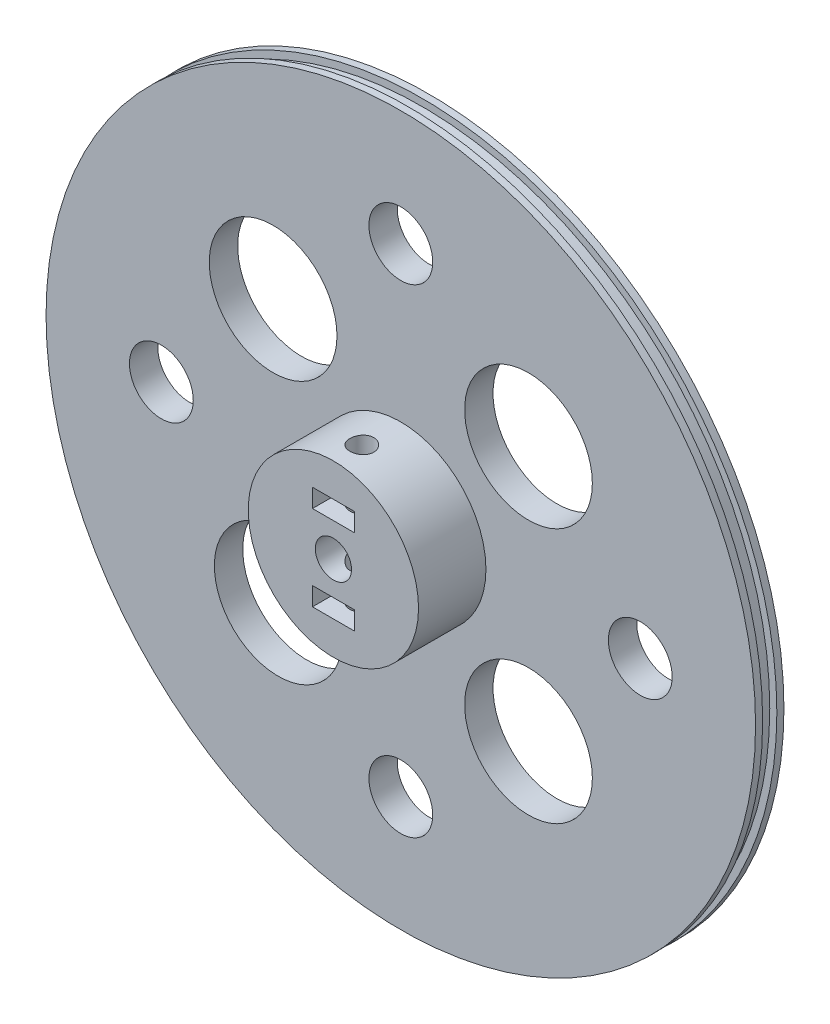
SolidWorks part; units mm, degrees
material "ABS"
ref_plane "Front Plane" through (0, 0, 0) normal (0, 0, 1) x (1, 0, 0)
ref_plane "Top Plane" through (0, 0, 0) normal (0, 1, 0) x (1, 0, 0)
ref_plane "Right Plane" through (0, 0, 0) normal (1, 0, 0) x (0, 0, -1)
sketch "Sketch1" plane through (0, 0, 0) normal (1, 0, 0) x (0, 0, -1)
  line L0 (0, 0) -> (0, 50)
  line L1 (0, 50) -> (-1, 50)
  line L2 (-1, 50) -> (-1, 49)
  line L3 (-1, 49) -> (-3, 49)
  line L4 (-3, 49) -> (-3, 50)
  line L5 (-3, 50) -> (-4, 50)
  line L6 (-4, 50) -> (-4, 12)
  line L7 (-4, 12) -> (-13.5, 12)
  line L8 (-13.5, 12) -> (-13.5, 0)
  line L9 (-13.5, 0) -> (0, 0)
  dimension "D1" = 50
  dimension "D2" = 1
  dimension "D3" = 2
  dimension "D4" = 1
  dimension "D5" = 9.5
  dimension "D6" = 12
  dimension "D7" = 1
revolve "Revolve2" add sketch "Sketch1" angle 360 about L9
sketch "Sketch2" plane through (0, 0, 13.5) normal (0, 0, 1) x (1, 0, 0)
  circle A0 centre (0, 0) radius 2.55
extrude "Cut-Extrude1" cut sketch "Sketch2" against normal blind 36
sketch "Sketch3" plane through (0, 0, 13.5) normal (0, 0, 1) x (1, 0, 0)
  line L1 (-2.95, 4.7) -> (2.95, 4.7)
  line L2 (-2.95, 4.7) -> (-2.95, 7.3)
  line L3 (-2.95, 7.3) -> (2.95, 7.3)
  line L4 (2.95, 4.7) -> (2.95, 7.3)
  line L5 (-2.95, 4.7) -> (2.95, 7.3) construction
  line L6 (-2.95, 7.3) -> (2.95, 4.7) construction
  line L7 (-2.95, -4.7) -> (2.95, -4.7)
  line L8 (-2.95, -4.7) -> (-2.95, -7.3)
  line L9 (-2.95, -7.3) -> (2.95, -7.3)
  line L10 (2.95, -4.7) -> (2.95, -7.3)
  line L11 (-2.95, -4.7) -> (2.95, -7.3) construction
  line L12 (-2.95, -7.3) -> (2.95, -4.7) construction
  point P0 (0, 6)
  point P5 (0, -6)
  dimension "D3" = 5.9
  dimension "D4" = 2.6
  dimension "D5" = 5.9
  dimension "D6" = 2.6
extrude "Cut-Extrude2" cut sketch "Sketch3" against normal blind 11
sketch "Sketch4" plane through (0, 0, 4) normal (0, 0, 1) x (1, 0, 0)
  circle A0 centre (0, 33.75) radius 4.5
  circle A1 centre (0, -33.75) radius 4.5
  circle A2 centre (33.75, 0) radius 4.5
  circle A3 centre (-33.75, 0) radius 4.5
  circle A4 centre (-17.9959, 17.9959) radius 9
  circle A5 centre (17.9959, 17.9959) radius 9
  circle A6 centre (17.9959, -17.9959) radius 9
  circle A7 centre (-17.2753, -18.6887) radius 9
extrude "Cut-Extrude3" cut sketch "Sketch4" against normal blind 11
sketch "Sketch5" plane through (0, 4.7, 0) normal (0, 1, 0) x (1, 0, 0)
  circle A1 centre (0, -9.5) radius 1.6823
extrude "Cut-Extrude4" cut sketch "Sketch5" against normal blind 81 and the other way blind 61
